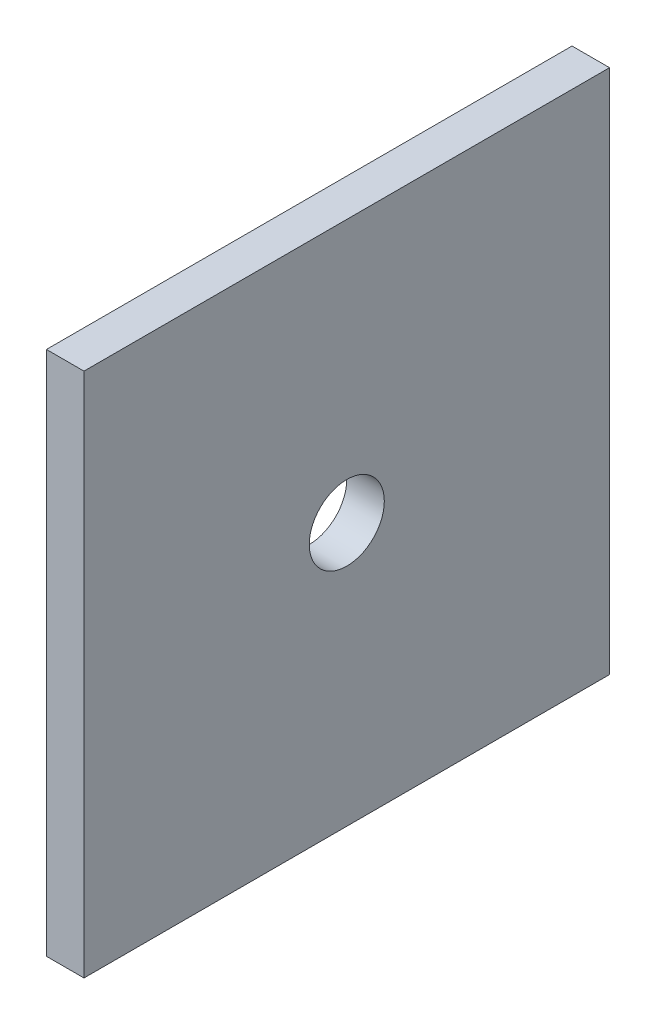
SolidWorks part; units mm, degrees
ref_plane "Front Plane" through (0, 0, 0) normal (0, 0, 1) x (1, 0, 0)
ref_plane "Top Plane" through (0, 0, 0) normal (0, 1, 0) x (1, 0, 0)
ref_plane "Right Plane" through (0, 0, 0) normal (1, 0, 0) x (0, 0, -1)
sketch "Sketch1" plane through (0, 0, 0) normal (1, 0, 0) x (0, 0, -1)
  line L1 (35, -35) -> (-35, -35)
  line L2 (35, -35) -> (35, 35)
  line L3 (35, 35) -> (-35, 35)
  line L4 (-35, -35) -> (-35, 35)
  line L5 (35, -35) -> (-35, 35) construction
  line L6 (35, 35) -> (-35, -35) construction
  circle A0 centre (0, 0) radius 5
  point P0 (0, 0)
  dimension "D3" = 10
  dimension "D1" = 70
  dimension "D2" = 70
extrude "Boss-Extrude1" add sketch "Sketch1" along normal blind 5
